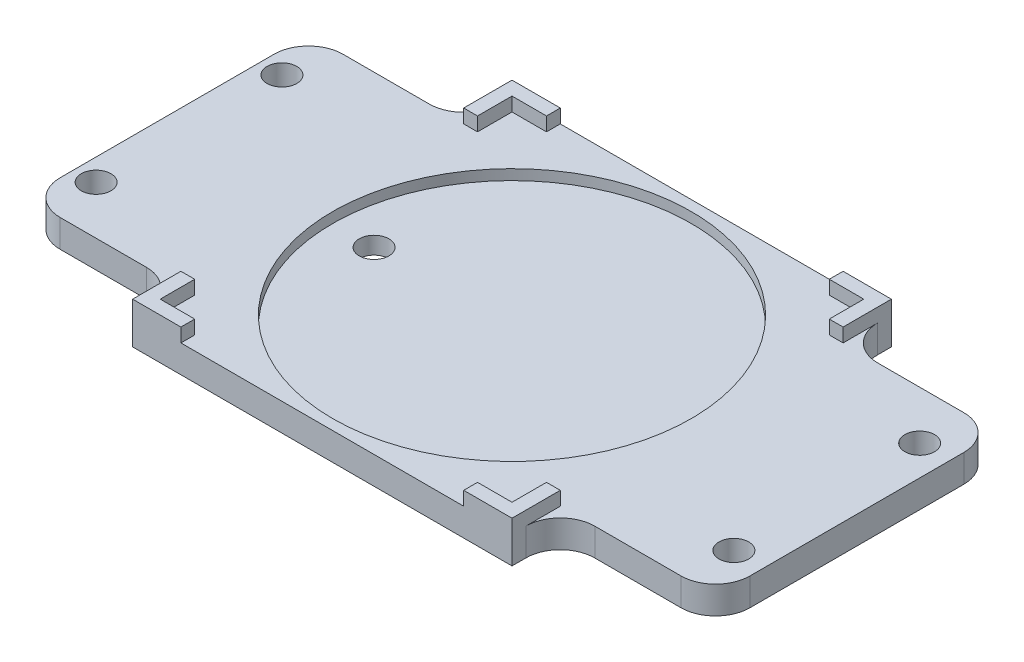
SolidWorks part; units mm, degrees
ref_plane "Front Plane" through (0, 0, 0) normal (0, 0, 1) x (1, 0, 0)
ref_plane "Top Plane" through (0, 0, 0) normal (0, 1, 0) x (1, 0, 0)
ref_plane "Right Plane" through (0, 0, 0) normal (1, 0, 0) x (0, 0, -1)
sketch "Sketch1" plane through (0, 0, 0) normal (0, 1, 0) x (1, 0, 0)
  line L1 (-50, 27.5) -> (50, 27.5)
  line L2 (-50, 27.5) -> (-50, -27.5)
  line L3 (-50, -27.5) -> (50, -27.5)
  line L4 (50, 27.5) -> (50, -27.5)
  line L5 (-50, 27.5) -> (50, -27.5) construction
  line L6 (-50, -27.5) -> (50, 27.5) construction
  point P0 (0, 0)
  dimension "D1" = 55
  dimension "D2" = 100
extrude "Boss-Extrude1" add sketch "Sketch1" along normal blind 4
hole_wizard "#6 Clearance Hole1" positions "Sketch2" profile "Sketch3" hole size "#6" standard "ANSI Inch" end condition through all
sketch "Sketch2" plane through (0, 4, 0) normal (0, 1, 0) x (1, 0, 0)
  arc A0 (45.6352, 12.1178) -> (45.6352, 14.8229) centre (45.6352, 13.4704) ccw construction
  arc A1 (45.6352, -14.8229) -> (45.6352, -12.1178) centre (45.6352, -13.4704) ccw construction
  arc A2 (-46.825, 14.8229) -> (-46.825, 12.1178) centre (-46.825, 13.4704) ccw construction
  arc A3 (-46.825, -12.1178) -> (-46.825, -14.8229) centre (-46.825, -13.4704) ccw construction
  point P0 (45.6352, 13.4704)
  point P2 (45.6352, -13.4704)
  point P4 (-46.825, -13.4704)
  point P6 (-46.825, 13.4704)
  point P23 (-20, 0)
  point P27 (0, 0)
  dimension "D1" = 20
sketch "Sketch3" plane through (45.6352, 4, -13.4704) normal (1, 0, 0) x (0, 0, 1)
  line L0 (0, 0) -> (0, 4)
  line L1 (0, 4) -> (2.1526, 4)
  line L2 (2.1526, 4) -> (2.1526, 0)
  line L5 (2.1526, 0) -> (0, 0)
  line L11 (0, -6.35) -> (0, 107.95) construction
  dimension "Thru Hole Dia." = 4.3053
  dimension "Thru Hole Depth" = 4
sketch "Sketch4" plane through (0, 4, 0) normal (0, 1, 0) x (1, 0, 0)
  circle A0 centre (0, 0) radius 26
  dimension "D1" = 52
extrude "Cut-Extrude1" cut sketch "Sketch4" against normal blind 1.5
sketch "Sketch6" plane through (0, 4, 0) normal (0, 1, 0) x (1, 0, 0)
  line L0 (-20.5, 25.5) -> (-20.5, 27.5)
  line L2 (50, 27.5) -> (-50, 27.5) construction
  line L3 (-20.5, 27.5) -> (-27.5, 27.5)
  line L4 (-27.5, 27.5) -> (-27.5, 20.5)
  line L5 (-27.5, 20.5) -> (-25.5, 20.5)
  line L7 (-25.5, 20.5) -> (-25.5, 25.5)
  line L8 (-25.5, 25.5) -> (-20.5, 25.5)
  point P2 (-25.8043, 25.9418)
  point P3 (0, 0)
  dimension "D1" = 5
extrude "Boss-Extrude2" add sketch "Sketch6" along normal blind 2
sketch "Sketch7" plane through (0, 4, 0) normal (0, 1, 0) x (1, 0, 0)
  line L1 (-50, 27.5) -> (-27.5, 27.5)
  line L2 (-50, 27.5) -> (-50, 20.5)
  line L3 (-50, 20.5) -> (-27.5, 20.5)
  line L4 (-27.5, 27.5) -> (-27.5, 20.5)
extrude "Cut-Extrude2" cut sketch "Sketch7" against normal up to next
mirror "Mirror1" about plane through (0, 0, 0) normal (0, 0, 1) of "Boss-Extrude2", "Cut-Extrude2"
mirror "Mirror2" about plane through (0, 0, 0) normal (1, 0, 0) of "Mirror1", "Boss-Extrude2", "Cut-Extrude2"
fillet "Fillet1" radius 5 8 edges at (-50, 2, -20.5) (-27.5, 2, -20.5) (50, 2, -20.5) (27.5, 2, -20.5) (50, 2, 20.5) (27.5, 2, 20.5) (-27.5, 2, 20.5) (-50, 2, 20.5)
equation "\"1é5\"=2"
